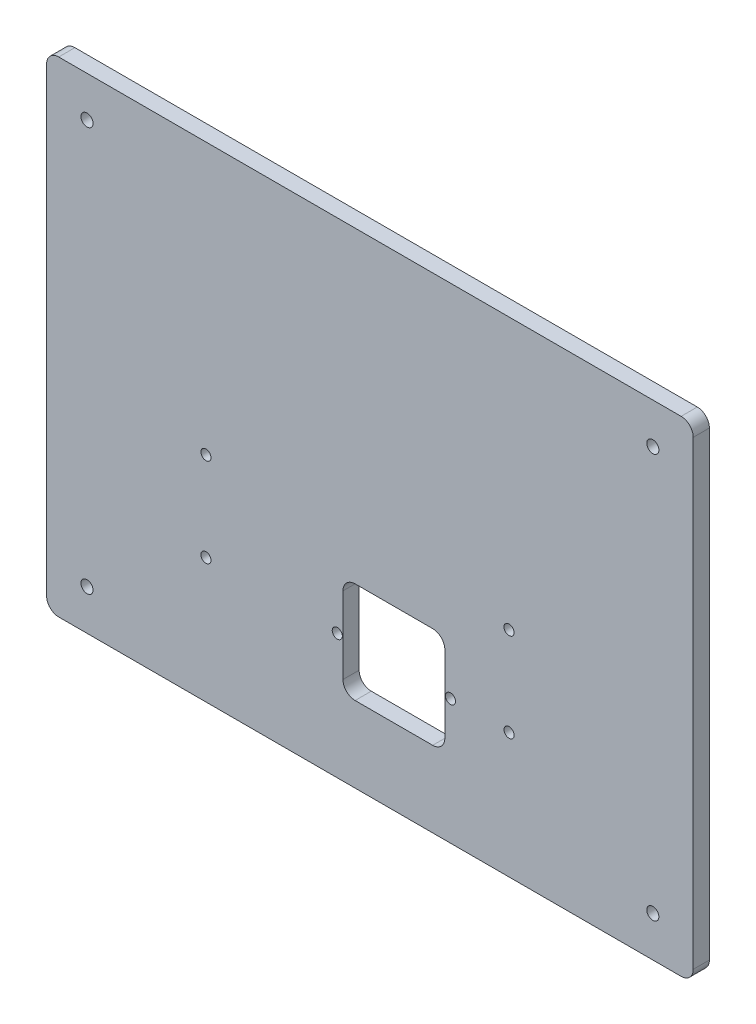
SolidWorks part; units mm, degrees
material "A-玻璃纤维"
ref_plane "前视基准面" through (0, 0, 0) normal (0, 0, 1) x (1, 0, 0)
ref_plane "上视基准面" through (0, 0, 0) normal (0, 1, 0) x (1, 0, 0)
ref_plane "右视基准面" through (0, 0, 0) normal (1, 0, 0) x (0, 0, -1)
other "Configuration Table"
sketch "草图1" plane through (0, 0, 0) normal (0, 0, 1) x (1, 0, 0)
  line L1 (-47.5, 60) -> (47.5, 60)
  line L2 (-47.5, 60) -> (-47.5, -60)
  line L3 (-47.5, -60) -> (47.5, -60)
  line L4 (47.5, 60) -> (47.5, -60)
  line L5 (-47.5, 60) -> (47.5, -60) construction
  line L6 (-47.5, -60) -> (47.5, 60) construction
  point P0 (0, 0)
  dimension "D1" = 95
  dimension "D2" = 120
extrude "凸台-拉伸1" add sketch "草图1" along normal blind 4 contours L2 L1 L4 L3
sketch "草图2" plane through (0, 0, 4) normal (0, 0, 1) x (1, 0, 0)
  line L0 (-47.5, 60) -> (47.5, 60) construction
  line L1 (-47.5, 60) -> (-47.5, -60) construction
  circle A0 centre (-33.75, 53) radius 1.3
  circle A1 centre (33.75, 53) radius 1.3
  circle A2 centre (-22, -3) radius 1.3
  circle A3 centre (22, -3) radius 1.3
  dimension "D1" = 2.6
  dimension "D3" = 2.6
  dimension "D5" = 67.5
  dimension "D6" = 44
  dimension "D7" = 56
  dimension "D8" = 7
  dimension "D9" = 13.75
  dimension "D10" = 25.5
  dimension "D2" = 2
  dimension "D4" = 2
fillet "圆角1" radius 3 4 edges at (47.5, -60, 2) (-47.5, -60, 2) (47.5, 60, 2) (-47.5, 60, 2)
sketch "草图4" plane through (0, 0, 4) normal (0, 0, 1) x (1, 0, 0)
  line L0 (-44.5, 60) -> (44.5, 60) construction
  line L1 (-44.5, 57) -> (44.5, 57)
  line L2 (-44.5, 57) -> (-44.5, -57)
  line L3 (-44.5, -57) -> (44.5, -57)
  line L4 (44.5, 57) -> (44.5, -57)
  line L5 (-80.5, 60) -> (79.5, 60)
  line L6 (-80.5, 60) -> (-80.5, -60)
  line L7 (-80.5, -60) -> (79.5, -60)
  line L8 (79.5, 60) -> (79.5, -60)
  arc A0 (44.5, -60) -> (47.5, -57) centre (44.5, -57) ccw construction
  dimension "D1" = 160
  dimension "D2" = 120
  dimension "D3" = 35
extrude "凸台-拉伸2" add sketch "草图4" against normal up to surface (4 mm away) up to face at (0, 0, 0)
sketch "草图5" plane through (0, 0, 4) normal (0, 0, 1) x (1, 0, 0)
  line L0 (79.5, 60) -> (-80.5, 60) construction
  line L1 (-80.5, 60) -> (-80.5, -60) construction
  line L2 (79.5, -60) -> (79.5, 60) construction
  line L3 (-80.5, -60) -> (79.5, -60) construction
  circle A0 centre (-70.5, 50) radius 1.5
  circle A1 centre (69.5, 50) radius 1.5
  circle A2 centre (69.5, -50) radius 1.5
  circle A3 centre (-70.5, -50) radius 1.5
  dimension "D1" = 3
  dimension "D2" = 10
  dimension "D3" = 10
  dimension "D6" = 10
  dimension "D7" = 10
  dimension "D8" = 10
  dimension "D4" = 2
  dimension "D5" = 2
sketch "草图6" plane through (0, 0, 4) normal (0, 0, 1) x (1, 0, 0)
  circle A0 centre (19.4255, -29.0234) radius 1.25
  circle A1 centre (-8.5745, -29.0234) radius 1.2508
  circle A2 centre (-41.0745, -7.0234) radius 1.25
  circle A3 centre (-41.0745, -29.0234) radius 1.25
  circle A4 centre (33.9255, -29.0234) radius 1.25
  circle A5 centre (33.9255, -7.0234) radius 1.25
  dimension "D1" = 2.5
  dimension "D2" = 2.5017
  dimension "D3" = 2.5
  dimension "D4" = 2.5
  dimension "D5" = 2.5
  dimension "D6" = 2.5
extrude "切除-拉伸3" cut sketch "草图6" against normal through all
sketch "草图7" plane through (0, 0, 0) normal (0, 0, -1) x (-1, 0, 0)
  line L0 (80.5, -60) -> (-79.5, -60) construction
  line L1 (7.1667, -16.2241) -> (-18.0333, -16.2241)
  line L2 (7.1667, -16.2241) -> (7.1667, -41.2241)
  line L3 (7.1667, -41.2241) -> (-18.0333, -41.2241)
  line L4 (-18.0333, -16.2241) -> (-18.0333, -41.2241)
  line L5 (-79.5, -60) -> (-79.5, 60) construction
  dimension "D1" = 25
  dimension "D2" = 25.2
  dimension "D3" = 18.7759
  dimension "D4" = 61.4667
extrude "切除-拉伸4" cut sketch "草图7" against normal through all
fillet "圆角3" radius 3 8 edges at (18.0333, -16.2241, 2) (18.0333, -41.2241, 2) (-7.1667, -41.2241, 2) (-7.1667, -16.2241, 2) (-80.5, 60, 2) (79.5, 60, 2) (79.5, -60, 2) (-80.5, -60, 2)
sketch "草图8" plane through (0, 0, 0) normal (0, 0, -1) x (-1, 0, 0)
  circle A0 centre (70.5, -50) radius 1.5
  circle A1 centre (70.5, 50) radius 1.5
  circle A2 centre (-69.5, 50) radius 1.5
  circle A3 centre (-69.5, -50) radius 1.5
  dimension "D1" = 3
  dimension "D2" = 3
  dimension "D3" = 3
  dimension "D4" = 3
extrude "切除-拉伸5" cut sketch "草图8" against normal through all
